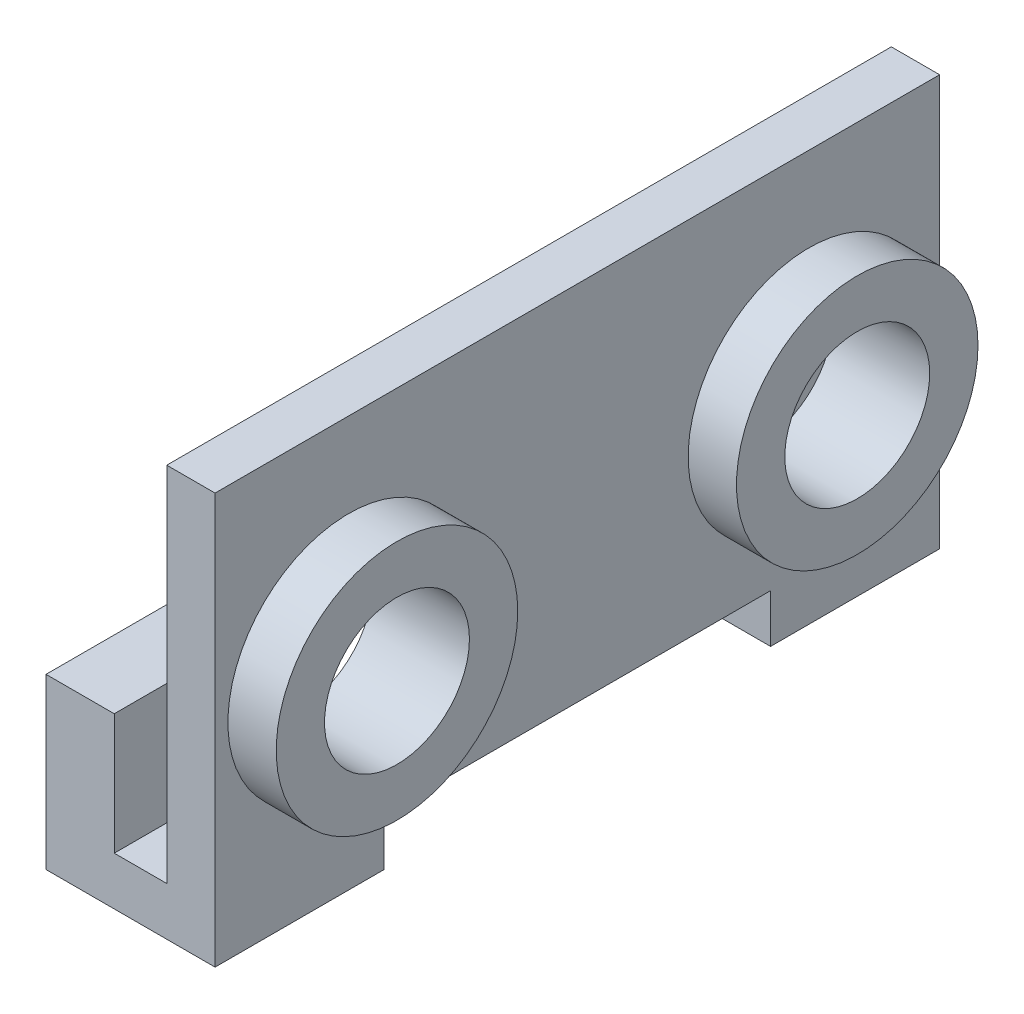
SolidWorks part; units mm, degrees
ref_plane "Front Plane" through (0, 0, 0) normal (0, 0, 1) x (1, 0, 0)
ref_plane "Top Plane" through (0, 0, 0) normal (0, 1, 0) x (1, 0, 0)
ref_plane "Right Plane" through (0, 0, 0) normal (1, 0, 0) x (0, 0, -1)
sketch "Esquisse1" plane through (0, 0, 0) normal (1, 0, 0) x (0, 0, -1)
  line L1 (-15, 8.5) -> (15, 8.5)
  line L2 (-15, 8.5) -> (-15, -8.5)
  line L3 (-15, -8.5) -> (15, -8.5)
  line L4 (15, 8.5) -> (15, -8.5)
  line L5 (-15, 8.5) -> (15, -8.5) construction
  line L6 (-15, -8.5) -> (15, 8.5) construction
  point P0 (0, 0)
extrude "Boss.-Extru.1" add sketch "Esquisse1" along normal blind 2
sketch "Esquisse2" plane through (2, 0, 0) normal (1, 0, 0) x (0, 0, -1)
  circle A0 centre (-9.4678, 0) radius 5
  circle A1 centre (9.5886, 0) radius 5
extrude "Boss.-Extru.2" add sketch "Esquisse2" along normal blind 2 contours A1 | A0
sketch "Esquisse3" plane through (4, 0, 0) normal (1, 0, 0) x (0, 0, -1)
  circle A0 centre (-9.4678, 0) radius 3
extrude "Enlèv. mat.-Extru.1" cut sketch "Esquisse3" against normal through all contours A0
sketch "Esquisse4" plane through (4, 0, 0) normal (1, 0, 0) x (0, 0, -1)
  circle A0 centre (9.5886, 0) radius 3
extrude "Enlèv. mat.-Extru.2" cut sketch "Esquisse4" against normal through all
ref_plane "Plan1" through (0, 0, 0) normal (0, 0, 1) x (1, 0, 0)
sketch "Esquisse7" plane through (0, -8.5, 0) normal (0, -1, 0) x (1, 0, 0)
  line L0 (0, 0) -> (2, 0) construction
  line L1 (0, 15) -> (0, -15) construction
  line L2 (2, 15) -> (2, -15) construction
  line L4 (0, 8) -> (2, 8)
  line L5 (0, 8) -> (0, 0)
  line L6 (0, 0) -> (2, 0)
  line L7 (2, 8) -> (2, 0)
extrude "Enlèv. mat.-Extru.3" cut sketch "Esquisse7" against normal blind 2
mirror "Symétrie1" about plane through (0, 0, 0) normal (0, 0, 1) of "Enlèv. mat.-Extru.3"
sketch "Esquisse8" plane through (0, 0, 0) normal (-1, 0, 0) x (0, 0, 1)
  line L1 (-15, -8.5) -> (-8, -8.5)
  line L2 (-15, -8.5) -> (-15, -6.5)
  line L3 (-15, -6.5) -> (-8, -6.5)
  line L4 (-8, -8.5) -> (-8, -6.5)
extrude "Boss.-Extru.3" add sketch "Esquisse8" along normal blind 5
sketch "Esquisse12" plane through (0, -6.5, 0) normal (0, 1, 0) x (1, 0, 0)
  line L0 (-5, 8) -> (0, 8) construction
  line L1 (-5, 15) -> (-2.1741, 15)
  line L2 (-5, 15) -> (-5, 8)
  line L3 (-5, 8) -> (-2.1741, 8)
  line L4 (-2.1741, 15) -> (-2.1741, 8)
extrude "Boss.-Extru.4" add sketch "Esquisse12" along normal blind 5
mirror "Symétrie2" about plane through (0, 0, 0) normal (0, 0, 1) of "Boss.-Extru.4", "Boss.-Extru.3"
